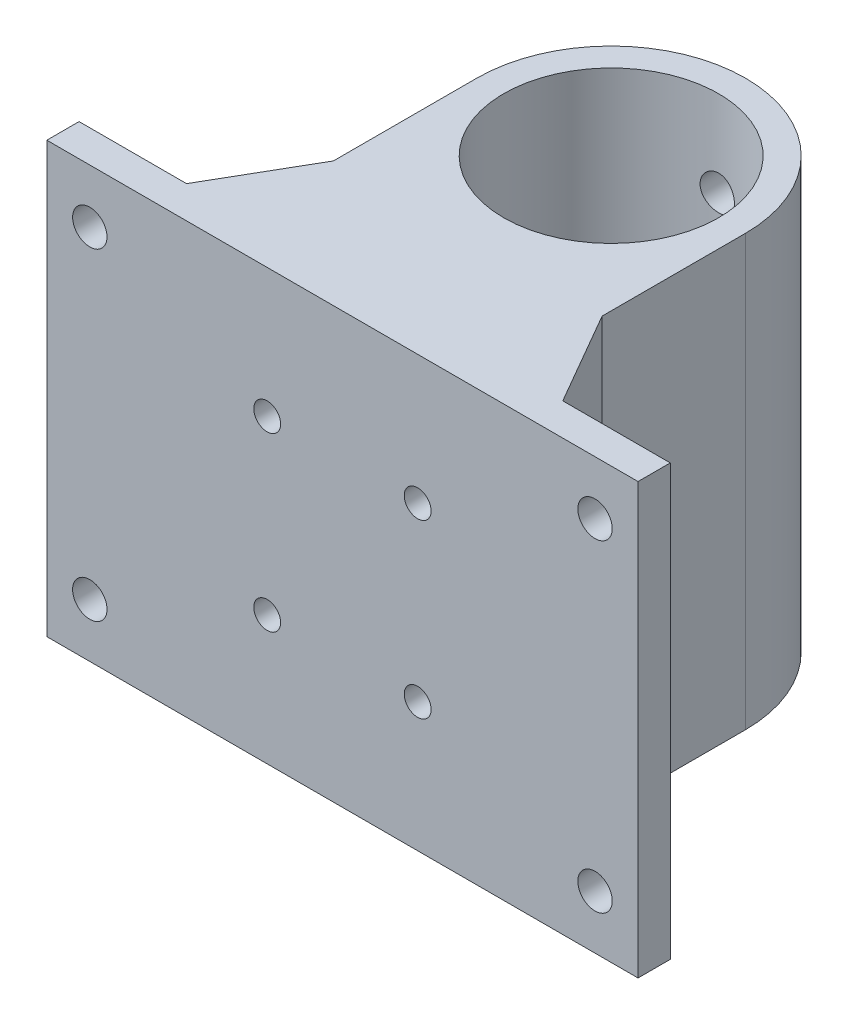
SolidWorks part; units mm, degrees
material "6061 合金"
ref_plane "前视基准面" through (0, 0, 0) normal (0, 0, 1) x (1, 0, 0)
ref_plane "上视基准面" through (0, 0, 0) normal (0, 1, 0) x (1, 0, 0)
ref_plane "右视基准面" through (0, 0, 0) normal (1, 0, 0) x (0, 0, -1)
sketch "草图1" plane through (0, 0, 0) normal (0, 1, 0) x (1, 0, 0)
  line L2 (-12.5, -25) -> (12.5, -25)
  line L3 (-12.5, -25) -> (-12.5, 0)
  line L5 (12.5, -25) -> (12.5, 0)
  arc A0 (12.5, 0) -> (-12.5, 0) centre (0, 0) ccw
  circle A1 centre (0, 0) radius 10
  point P3 (0, -12.5)
  dimension "D1" = 25
  dimension "D3" = 20
extrude "凸台-拉伸1" add sketch "草图1" along normal mid plane 40
sketch "草图7" plane through (0, 0, 0) normal (0, 0, 1) x (1, 0, 0)
  line L0 (0, 0) -> (9.3494, 0) construction
  line L1 (0, -12) -> (0, 12) construction
  line L2 (0, 0) -> (-12.5, 0) construction
  line L3 (-12.5, 20) -> (-12.5, -20) construction
  circle A0 centre (0, -12) radius 1.6
  circle A1 centre (0, 12) radius 1.6
  dimension "D1" = 12
extrude "切除-拉伸2" cut sketch "草图7" against normal through all
hole_wizard "M3 螺纹孔1" positions "3D草图1" profile "草图8" tap size "M3" standard "GB"
sketch3d "3D草图1"
  point P0 (-7, -8, 25)
  point P7 (7, -8, 25)
  point P9 (7, 8, 25)
  point P11 (-7, 8, 25)
sketch "草图8" plane through (-7, -8, 25) normal (1, 0, 0) x (0, -1, 0)
  line L0 (0, 0) -> (0, 10.2511)
  line L1 (0, 10.2511) -> (1.25, 9.5)
  line L2 (1.25, 9.5) -> (1.25, 0)
  line L5 (1.25, 0) -> (0, 0)
  line L10 (0, 10.2511) -> (-1.25, 9.5) construction
  line L11 (0, -6.35) -> (0, 107.95) construction
  dimension "螺纹孔钻头直径" = 2.5
  dimension "螺纹孔钻头深度" = 9.5
  dimension "导头角度" = 118
cosmetic thread "孔螺蚊线1" parameters "D1"=8, "D2"=3
cosmetic thread "孔螺蚊线2" parameters "D1"=8, "D2"=3
cosmetic thread "孔螺蚊线3" parameters "D1"=8, "D2"=3
cosmetic thread "孔螺蚊线4" parameters "D1"=8, "D2"=3
sketch "草图9" plane through (12.5, 0, 0) normal (1, 0, 0) x (0, 0, -1)
  line L0 (-25, 20) -> (0, 20) construction
  line L1 (-25, -20) -> (-22, -20)
  line L2 (-25, -20) -> (-25, 20)
  line L3 (-25, 20) -> (-22, 20)
  line L4 (-22, -20) -> (-22, 20)
  dimension "D1" = 3
extrude "凸台-拉伸2" add sketch "草图9" along normal blind 15
sketch "草图10" plane through (0, 0, 22) normal (0, 0, -1) x (-1, 0, 0)
  line L0 (-12.5, 0) -> (-27.5, 0) construction
  line L3 (-12.5, -20) -> (-12.5, 20) construction
  line L4 (-27.5, -20) -> (-27.5, 20) construction
  line L5 (-27.5, 20) -> (-12.5, 20) construction
  circle A0 centre (-23.5, 15) radius 1.6
  circle A1 centre (-23.5, -15) radius 1.6
  dimension "D1" = 4
  dimension "D2" = 3.2
  dimension "D3" = 5
extrude "切除-拉伸3" cut sketch "草图10" against normal through all
ref_plane "基准面1" through (0, 0, 0) normal (1, 0, 0) x (0, 0, -1)
mirror "镜向6" about plane through (0, 0, 0) normal (1, 0, 0) of "切除-拉伸3", "凸台-拉伸2"
chamfer "倒角1" distance 5 angle 60 2 edges at (12.5, 0, 22) (-12.5, 0, 22)
